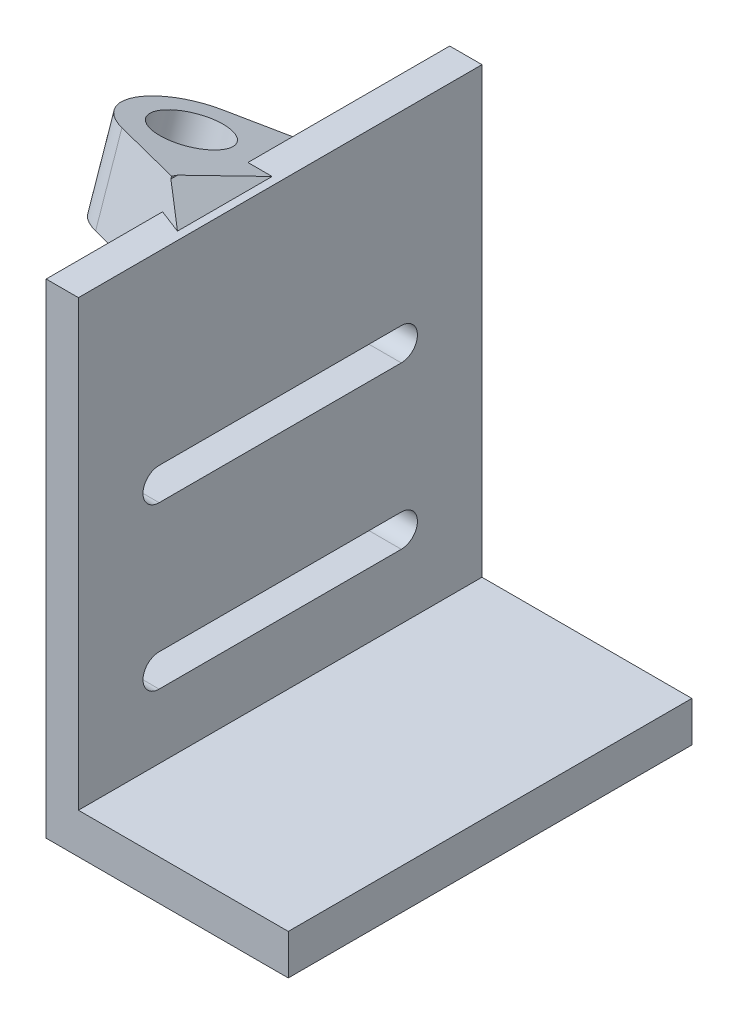
SolidWorks part; units mm, degrees
ref_plane "Plano frontal" through (0, 0, 0) normal (0, 0, 1) x (1, 0, 0)
ref_plane "Plano superior" through (0, 0, 0) normal (0, 1, 0) x (1, 0, 0)
ref_plane "Plano direito" through (0, 0, 0) normal (1, 0, 0) x (0, 0, -1)
sketch "Esboço2" plane through (0, 0, 0) normal (0, 0, 1) x (1, 0, 0)
  line L0 (0, 0) -> (30, 0)
  line L1 (30, 0) -> (30, 5)
  line L2 (30, 5) -> (4, 5)
  line L3 (4, 5) -> (4, 60)
  line L4 (4, 60) -> (0, 60)
  line L5 (0, 60) -> (0, 0)
  dimension "D1" = 5
  dimension "D2" = 30
  dimension "D3" = 4
  dimension "D4" = 60
extrude "Ressalto-extrusão1" add sketch "Esboço2" along normal blind 50
sketch "Esboço3" plane through (4, 0, 0) normal (1, 0, 0) x (0, 0, -1)
  line L0 (-25, 60) -> (-25, 5) construction
  line L1 (-50, 60) -> (0, 60) construction
  line L2 (-50, 5) -> (0, 5) construction
  line L3 (-40, 35) -> (-10, 35) construction
  line L4 (-40, 37) -> (-10, 37)
  line L5 (-40, 33) -> (-10, 33)
  line L6 (-40, 15) -> (-10, 15) construction
  line L7 (-40, 17) -> (-10, 17)
  line L8 (-40, 13) -> (-10, 13)
  arc A0 (-40, 37) -> (-40, 33) centre (-40, 35) ccw
  arc A1 (-10, 33) -> (-10, 37) centre (-10, 35) ccw
  arc A2 (-40, 17) -> (-40, 13) centre (-40, 15) ccw
  arc A3 (-10, 13) -> (-10, 17) centre (-10, 15) ccw
  point P8 (-25, 35)
  point P14 (-25, 15)
  dimension "D1" = 2
  dimension "D2" = 30
  dimension "D3" = 20
  dimension "D4" = 10
extrude "Corte-extrusão1" cut sketch "Esboço3" against normal blind 50
sketch "Esboço4" plane through (0, 0, 0) normal (-1, 0, 0) x (0, 0, 1)
  line L0 (25, 60) -> (21.5969, 69.8834) construction
  line L1 (50, 60) -> (0, 60) construction
  dimension "D1" = 71
sketch3d "3DSketch1"
  line L0 (0, 60, 25) -> (0, 69.8834, 21.5969) construction
  line L1 (4, 60, 0) -> (0, 60, 0) construction
  line L2 (0, 60, 25) -> (-7, 60, 25) construction
  line L3 (0, 60, 50) -> (0, 60, 0) construction
  line L4 (-9.396, 62.1413, 31.2188) -> (0, 63.2557, 34.4552)
  line L5 (0, 63.2557, 34.4552) -> (0, 56.7443, 15.5448)
  line L6 (0, 56.7443, 15.5448) -> (-9.396, 57.8587, 18.7812)
  circle A1 centre (-7, 60, 25) radius 4.15
  arc A2 (-9.396, 62.1413, 31.2188) -> (-9.396, 57.8587, 18.7812) centre (-7, 60, 25) ccw
  point P6 (-7, 53.3814, 27.279)
  point P7 (0, 0, 0)
  point P12 (-7, 56.0761, 26.3511)
  point P17 (0, 52.4512, 32.1187)
  point P18 (0, 47.0528, 16.4407)
  point P19 (0, 0, 0)
  point P20 (-1.9459, 47.4633, 17.633)
  point P21 (0, 0, 0)
  point P22 (-3.1438, 47.0015, 16.2917)
  point P23 (0, 60, 25)
  point P24 (-1.4744, 53.2201, 34.3518)
  point P25 (-0.8426, 47.0015, 16.2917)
  point P26 (-9.1638, 45.9441, 13.2209)
  point P27 (0, 52.793, 33.1114)
  dimension "D1" = 7
  dimension "D3" = 7
  dimension "D2" = 8.3
  dimension "D4" = 20
extrude "Ressalto-extrusão2" add sketch "3DSketch1" along direction (0, 0.9455, -0.3256) on the side of the normal blind 10
chamfer "Chanfro1" distance 3 angle 45 1 edges at (0, 60, 30.2881)
